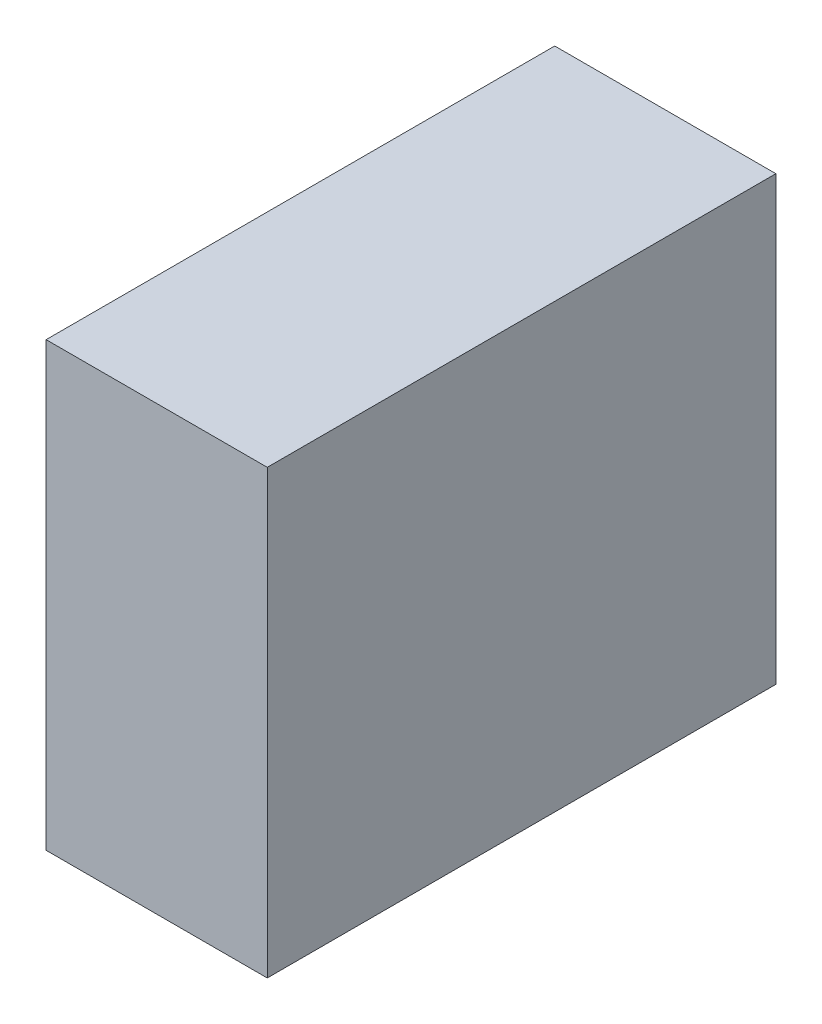
SolidWorks part; units mm, degrees
ref_plane "Front Plane" through (0, 0, 0) normal (0, 0, 1) x (1, 0, 0)
ref_plane "Top Plane" through (0, 0, 0) normal (0, 1, 0) x (1, 0, 0)
ref_plane "Right Plane" through (0, 0, 0) normal (1, 0, 0) x (0, 0, -1)
sketch "Sketch1" plane through (0, 0, 0) normal (1, 0, 0) x (0, 0, -1)
  line L1 (0, 0) -> (23, 0)
  line L2 (0, 0) -> (0, 20)
  line L3 (0, 20) -> (23, 20)
  line L4 (23, 0) -> (23, 20)
extrude "Boss-Extrude1" add sketch "Sketch1" along normal blind 10
